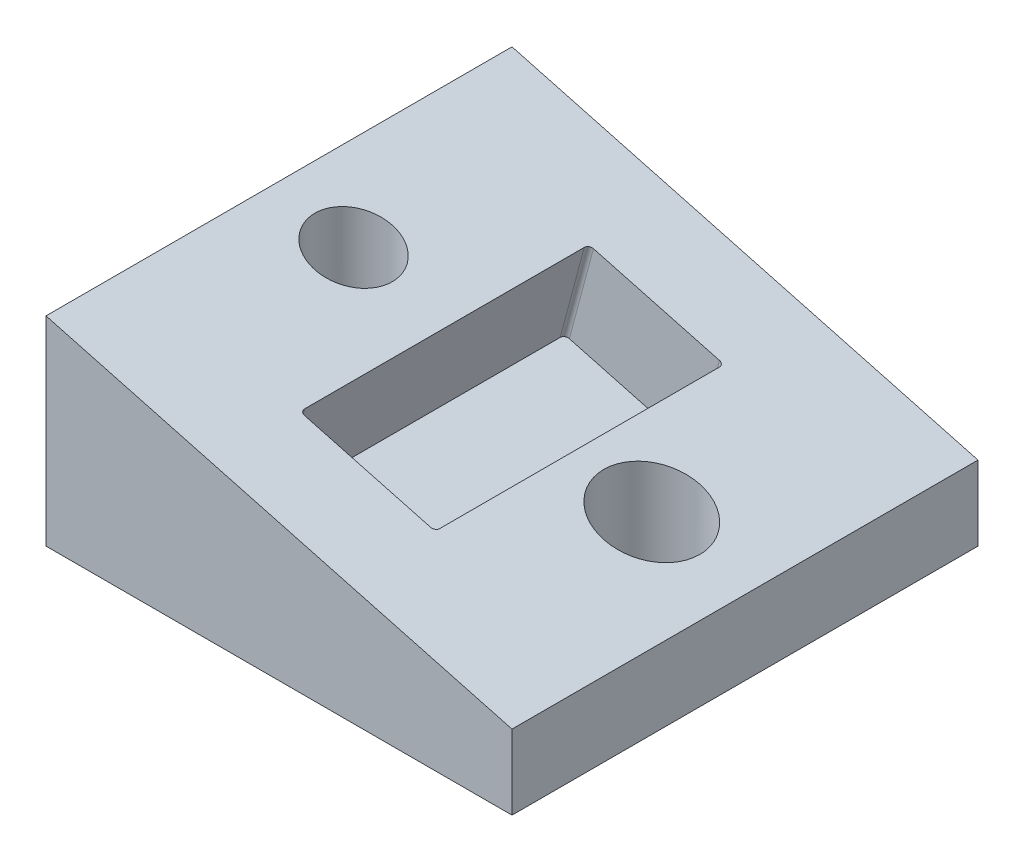
SolidWorks part; units mm, degrees
ref_plane "前视基准面" through (0, 0, 0) normal (0, 0, 1) x (1, 0, 0)
ref_plane "上视基准面" through (0, 0, 0) normal (0, 1, 0) x (1, 0, 0)
ref_plane "右视基准面" through (0, 0, 0) normal (1, 0, 0) x (0, 0, -1)
sketch "草图8" plane through (0, 0, 0) normal (0, 0, 1) x (1, 0, 0)
  line L0 (25, 4) -> (-25, 17.3975)
  line L2 (-25, 4) -> (-25, -4)
  line L3 (-25, -4) -> (25, -4)
  line L4 (25, 4) -> (25, -4)
  line L5 (0, -4) -> (0, 4) construction
  line L6 (-25, 0) -> (25, 0) construction
  line L7 (-25, -4) -> (-25, 17.3975)
  point P0 (0, 0)
  point P4 (0, 0)
  dimension "D1" = 50
  dimension "D2" = 8
extrude "凸台-拉伸8" add sketch "草图8" along normal blind 50 contours L7 L2 L3 L4 L0
sketch "草图9" plane through (0, -4, 0) normal (0, -1, 0) x (1, 0, 0)
  circle A0 centre (15, 25) radius 5.15
  circle A1 centre (-17, 25) radius 4.15
extrude "切除-拉伸2" cut sketch "草图9" against normal blind 50
sketch "草图10" plane through (2.6747, 9.9821, 0) normal (0.2588, 0.9659, 0) x (0.9659, -0.2588, 0)
  line L2 (4.7329, -40.5) -> (-10.2671, -40.5)
  line L5 (4.7329, -40.5) -> (4.7329, -9.5)
  line L6 (4.7329, -9.5) -> (-10.2671, -9.5)
  line L7 (-10.2671, -9.5) -> (-10.2671, -40.5)
extrude "切除-拉伸3" cut sketch "草图10" against normal blind 10
fillet "圆角1" radius 0.5 4 edges at (-8.5367, 7.8098, 40.5) (5.9522, 3.9275, 40.5) (-8.5367, 7.8098, 9.5) (5.9522, 3.9275, 9.5)
